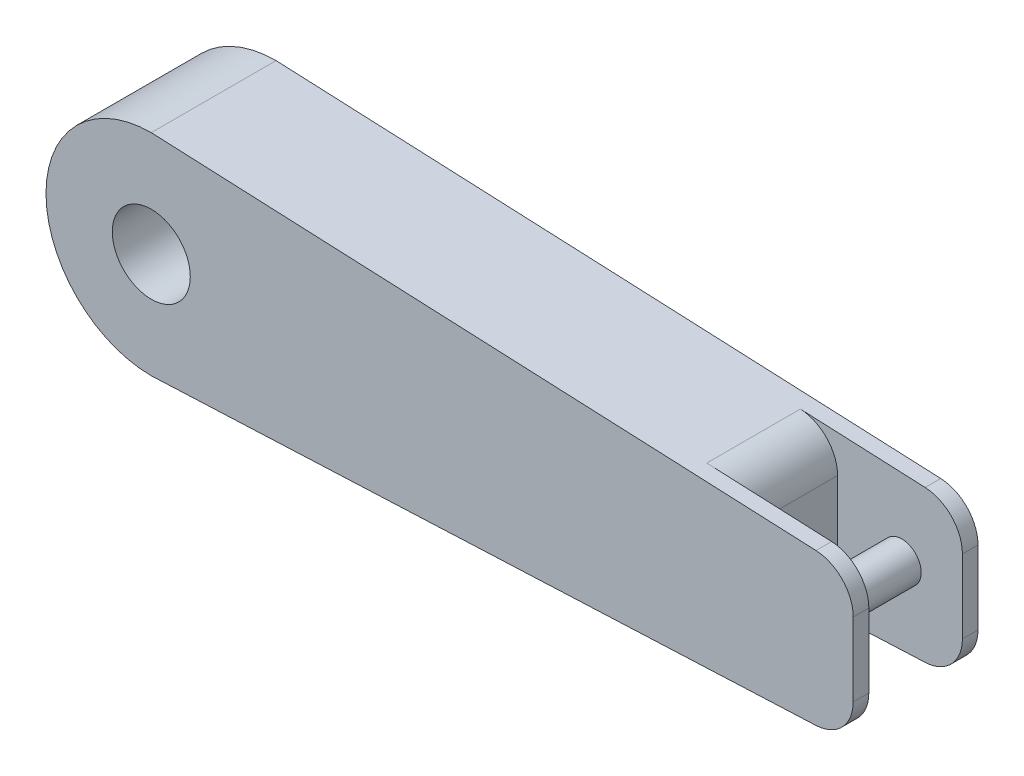
SolidWorks part; units mm, degrees
ref_plane "Front Plane" through (0, 0, 0) normal (0, 0, 1) x (1, 0, 0)
ref_plane "Top Plane" through (0, 0, 0) normal (0, 1, 0) x (1, 0, 0)
ref_plane "Right Plane" through (0, 0, 0) normal (1, 0, 0) x (0, 0, -1)
sketch "Sketch1" plane through (0, 0, 0) normal (0, 0, 1) x (1, 0, 0)
  line L4 (-151.5992, -67.5) -> (298.4008, -67.5)
  line L5 (298.4008, -67.5) -> (298.4008, 67.5)
  line L6 (298.4008, 67.5) -> (-151.5992, 67.5)
  arc A1 (-151.5992, 67.5) -> (-151.5992, -67.5) centre (-151.5992, 0) ccw
  circle A2 centre (-151.5992, 0) radius 25
  point P8 (286.3471, 19.5297)
  dimension "D1" = 50
  dimension "D4" = 67.5
  dimension "D2" = 450
  dimension "D3" = 135
  dimension "D5" = 298.4008
extrude "Boss-Extrude1" add sketch "Sketch1" along normal blind 80 contours L6 A1 L4 L5
sketch "Sketch3" plane through (0, 0, 80) normal (0, 0, 1) x (1, 0, 0)
  line L0 (-151.5992, 67.5) -> (298.4008, 47.5)
  line L1 (298.4008, -67.5) -> (298.4008, 67.5) construction
  line L2 (298.4008, 47.5) -> (298.4008, -47.5)
  line L3 (298.4008, -47.5) -> (-151.5992, -67.5)
  line L4 (-151.5992, -67.5) -> (298.4008, -67.5)
  line L5 (298.4008, -67.5) -> (298.4008, -47.5)
  line L6 (298.4008, 47.5) -> (298.4008, 67.5)
  line L7 (298.4008, 67.5) -> (-151.5992, 67.5)
  line M6 (-151.5992, -67.5) -> (298.4008, -67.5)
  line M7 (298.4008, -67.5) -> (298.4008, 67.5)
  line M8 (298.4008, 67.5) -> (-151.5992, 67.5)
  dimension "D1" = 20
  dimension "D2" = 20
extrude "Cut-Extrude1" cut sketch "Sketch3" against normal blind 80 contours L0 M8 M7 | L3 M7 M6
sketch "Sketch4" plane through (298.4008, 0, 0) normal (1, 0, 0) x (0, 0, -1)
  line L0 (-80, -47.5) -> (-80, 47.5) construction
  line L1 (-70, 72.5) -> (-10, 72.5)
  line L2 (-70, 72.5) -> (-70, -72.5)
  line L3 (-70, -72.5) -> (-10, -72.5)
  line L4 (-10, 72.5) -> (-10, -72.5)
  line L5 (0, -47.5) -> (0, 47.5) construction
  line L6 (0, -47.5) -> (-80, -47.5) construction
  line L7 (0, 47.5) -> (-80, 47.5) construction
  dimension "D1" = 10
  dimension "D2" = 10
  dimension "D3" = 25
  dimension "D4" = 25
extrude "Cut-Extrude2" cut sketch "Sketch4" against normal blind 80
fillet "Fillet1" radius 25 2 edges at (218.4008, -51.0556, 40) (218.4008, 51.0556, 40)
fillet "Fillet2" radius 25 4 edges at (298.4008, -47.5, 75) (298.4008, -47.5, 5) (298.4008, 47.5, 5) (298.4008, 47.5, 75)
sketch "Sketch5" plane through (0, 0, 10) normal (0, 0, 1) x (1, 0, 0)
  line L1 (274.5109, 48.5618) -> (274.5109, -48.5618) construction
  line L2 (274.5109, 0) -> (259.5109, 0) construction
  circle A1 centre (259.5109, 0) radius 12.5
  dimension "D1" = 25
  dimension "D2" = 15
extrude "Boss-Extrude2" add sketch "Sketch5" along normal up to surface (60 mm away) up to face at (248.9613, 0, 70)
